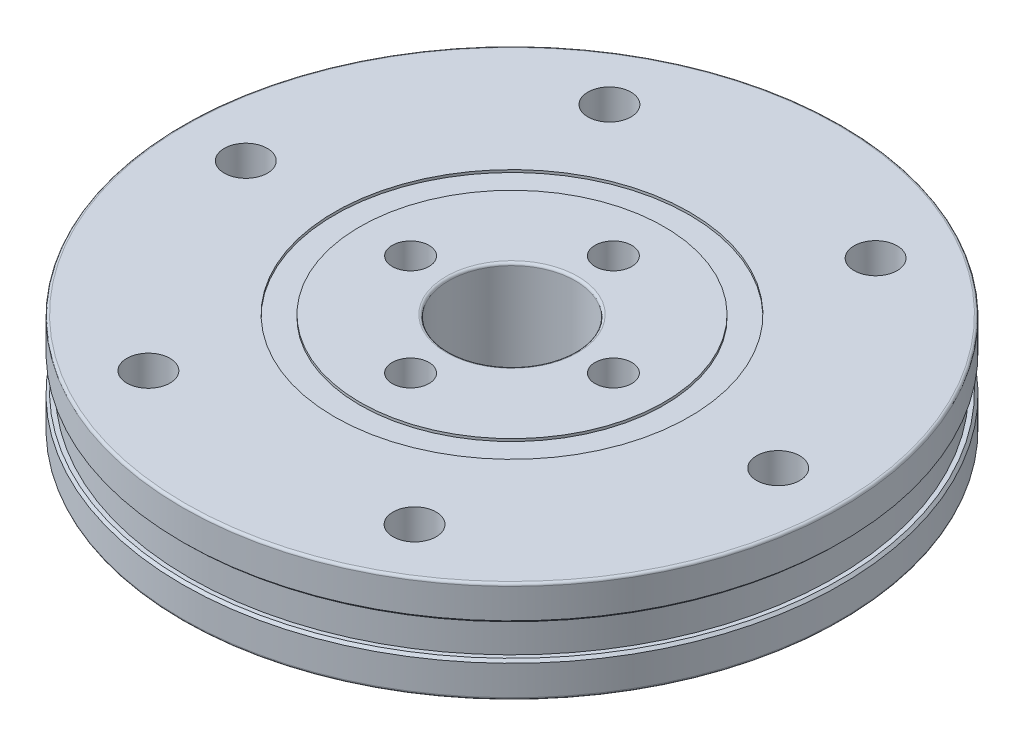
SolidWorks part; units mm, degrees
ref_plane "前视基准面" through (0, 0, 0) normal (0, 0, 1) x (1, 0, 0)
ref_plane "上视基准面" through (0, 0, 0) normal (0, 1, 0) x (1, 0, 0)
ref_plane "右视基准面" through (0, 0, 0) normal (1, 0, 0) x (0, 0, -1)
sketch "草图1" plane through (0, 0, 0) normal (0, 1, 0) x (1, 0, 0)
  line L1 (-21, 0) -> (-10.5, -18.1865) construction
  line L2 (-10.5, -18.1865) -> (10.5, -18.1865) construction
  line L3 (10.5, -18.1865) -> (21, 0) construction
  line L4 (21, 0) -> (10.5, 18.1865) construction
  line L5 (10.5, 18.1865) -> (-10.5, 18.1865) construction
  line L6 (-10.5, 18.1865) -> (-21, 0) construction
  line L7 (0, -8) -> (8, 0) construction
  line L8 (8, 0) -> (0, 8) construction
  line L9 (0, 8) -> (-8, 0) construction
  line L10 (-8, 0) -> (0, -8) construction
  circle A0 centre (0, 0) radius 5
  circle A1 centre (0, 0) radius 26
  circle A3 centre (0, 0) radius 21 construction
  circle A4 centre (0, 0) radius 18.1865 construction
  circle A5 centre (-10.5, 18.1865) radius 1.7
  circle A6 centre (10.5, 18.1865) radius 1.7
  circle A7 centre (21, 0) radius 1.7
  circle A8 centre (10.5, -18.1865) radius 1.7
  circle A9 centre (-10.5, -18.1865) radius 1.7
  circle A10 centre (-21, 0) radius 1.7
  circle A11 centre (0, 0) radius 8 construction
  circle A12 centre (0, 0) radius 5.6569 construction
  circle A13 centre (0, 8) radius 1.45
  circle A14 centre (8, 0) radius 1.45
  circle A15 centre (0, -8) radius 1.45
  circle A16 centre (-8, 0) radius 1.45
  point P27 (0.0837, 7.9996)
  point P30 (0.0739, -7.9261)
  dimension "D1" = 10
  dimension "D2" = 52
  dimension "D3" = 42
  dimension "D4" = 3.4
  dimension "D5" = 16
  dimension "D6" = 2.9
extrude "凸台-拉伸1" add sketch "草图1" along normal mid plane 8
sketch "草图2" plane through (0, 4, 0) normal (0, 1, 0) x (1, 0, 0)
  circle A0 centre (0, 0) radius 12
  circle A1 centre (0, 0) radius 14
  dimension "D1" = 24
  dimension "D2" = 28
extrude "切除-拉伸1" cut sketch "草图2" against normal blind 0.2 contours A1 | A0
sketch "草图3" plane through (0, -4, 0) normal (0, -1, 0) x (1, 0, 0)
  circle A0 centre (0, 0) radius 12
  circle A1 centre (0, 0) radius 14
  dimension "D1" = 24
  dimension "D2" = 28
extrude "切除-拉伸2" cut sketch "草图3" against normal blind 0.2
sketch "草图5" plane through (0, 0, 0) normal (0, 1, 0) x (1, 0, 0)
  circle A0 centre (0, 0) radius 27.9239
  circle A1 centre (0, 0) radius 25.4684
extrude "切除-拉伸3" cut sketch "草图5" against normal mid plane 2.5
chamfer "倒角1" distance 0.2 angle 45 2 edges at (0, -1.25, 26) (0, 1.25, 26)
fillet "圆角1" radius 0.2 4 edges at (0, -4, 5) (0, -4, 26) (0, 4, 5) (0, 4, 26)
sketch "草图6" plane through (0, -4, 0) normal (0, -1, 0) x (1, 0, 0)
  circle A0 centre (-21, 0) radius 3.25
  circle A1 centre (-10.5, -18.1865) radius 3.25
  circle A2 centre (10.5, -18.1865) radius 3.25
  circle A3 centre (21, 0) radius 3.25
  circle A4 centre (10.5, 18.1865) radius 3.25
  circle A5 centre (-10.5, 18.1865) radius 3.25
  dimension "D1" = 6.5
extrude "切除-拉伸4" cut sketch "草图6" against normal blind 3.3
